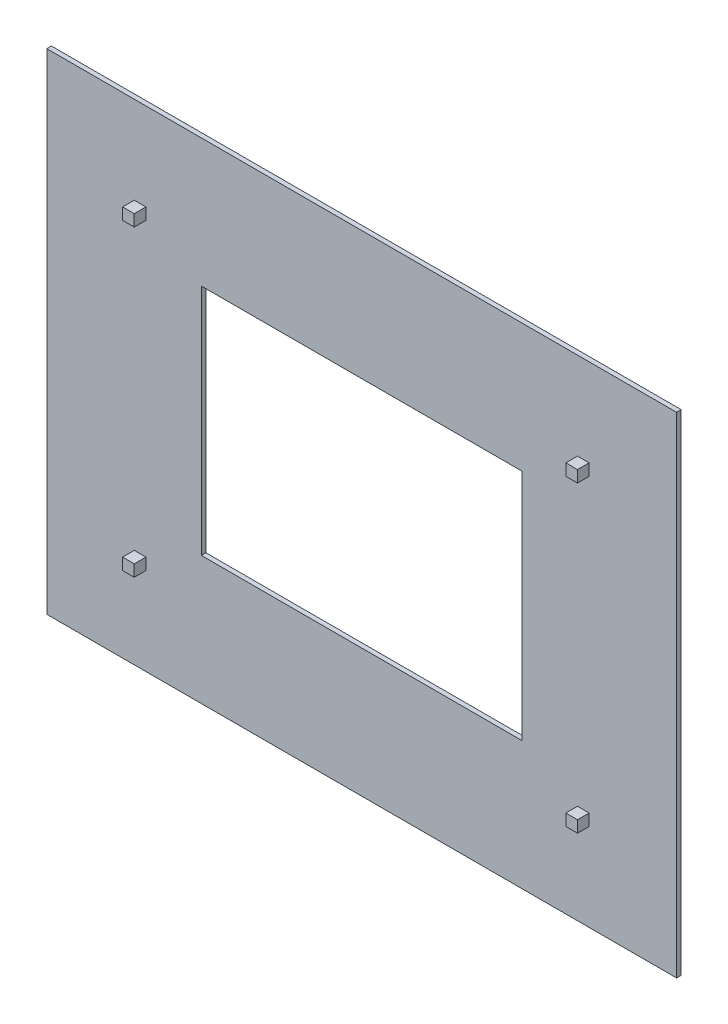
SolidWorks part; units mm, degrees
ref_plane "Front Plane" through (0, 0, 0) normal (0, 0, 1) x (1, 0, 0)
ref_plane "Top Plane" through (0, 0, 0) normal (0, 1, 0) x (1, 0, 0)
ref_plane "Right Plane" through (0, 0, 0) normal (1, 0, 0) x (0, 0, -1)
sketch "Sketch1" plane through (0, 0, 0) normal (0, 0, 1) x (1, 0, 0)
  line L1 (-68.58, 53.34) -> (68.58, 53.34)
  line L2 (-68.58, 53.34) -> (-68.58, -53.34)
  line L3 (-68.58, -53.34) -> (68.58, -53.34)
  line L4 (68.58, 53.34) -> (68.58, -53.34)
  line L5 (-68.58, 53.34) -> (68.58, -53.34) construction
  line L6 (-68.58, -53.34) -> (68.58, 53.34) construction
  point P0 (0, 0)
  dimension "D1" = 137.16
  dimension "D2" = 106.68
extrude "Boss-Extrude1" add sketch "Sketch1" along normal blind 1
sketch "Sketch4" plane through (0, 0, 1) normal (0, 0, 1) x (1, 0, 0)
  line L0 (-68.58, 53.34) -> (-68.58, -53.34) construction
  line L1 (-49.53, 34.29) -> (-46.99, 34.29)
  line L2 (-49.53, 34.29) -> (-49.53, 31.75)
  line L3 (-49.53, 31.75) -> (-46.99, 31.75)
  line L4 (-46.99, 34.29) -> (-46.99, 31.75)
  line L5 (-49.53, 34.29) -> (-46.99, 31.75) construction
  line L6 (-49.53, 31.75) -> (-46.99, 34.29) construction
  line L7 (68.58, 53.34) -> (-68.58, 53.34) construction
  line L8 (0, -55) -> (0, 55) construction
  line L9 (49.53, 31.75) -> (46.99, 31.75)
  line L10 (46.99, 34.29) -> (46.99, 31.75)
  line L11 (49.53, 34.29) -> (46.99, 34.29)
  line L12 (49.53, 34.29) -> (49.53, 31.75)
  line L13 (55, 0) -> (-55, 0) construction
  line L14 (49.53, -34.29) -> (49.53, -31.75)
  line L15 (49.53, -34.29) -> (46.99, -34.29)
  line L16 (46.99, -34.29) -> (46.99, -31.75)
  line L17 (49.53, -31.75) -> (46.99, -31.75)
  line L18 (-49.53, -31.75) -> (-46.99, -31.75)
  line L19 (-46.99, -34.29) -> (-46.99, -31.75)
  line L20 (-49.53, -34.29) -> (-46.99, -34.29)
  line L21 (-49.53, -34.29) -> (-49.53, -31.75)
  point P0 (-48.26, 33.02)
  dimension "D1" = 2.54
  dimension "D2" = 2.54
  dimension "D3" = 19.05
  dimension "D4" = 19.05
extrude "Boss-Extrude2" add sketch "Sketch4" along normal blind 2.54
sketch "Sketch5" plane through (0, 0, 1) normal (0, 0, 1) x (1, 0, 0)
  line L1 (-34.925, -25.4) -> (34.925, -25.4)
  line L2 (-34.925, -25.4) -> (-34.925, 25.4)
  line L3 (-34.925, 25.4) -> (34.925, 25.4)
  line L4 (34.925, -25.4) -> (34.925, 25.4)
  line L5 (-34.925, -25.4) -> (34.925, 25.4) construction
  line L6 (-34.925, 25.4) -> (34.925, -25.4) construction
  point P0 (0, 0)
  dimension "D1" = 69.85
  dimension "D2" = 50.8
extrude "Cut-Extrude1" cut sketch "Sketch5" against normal blind 2.54
